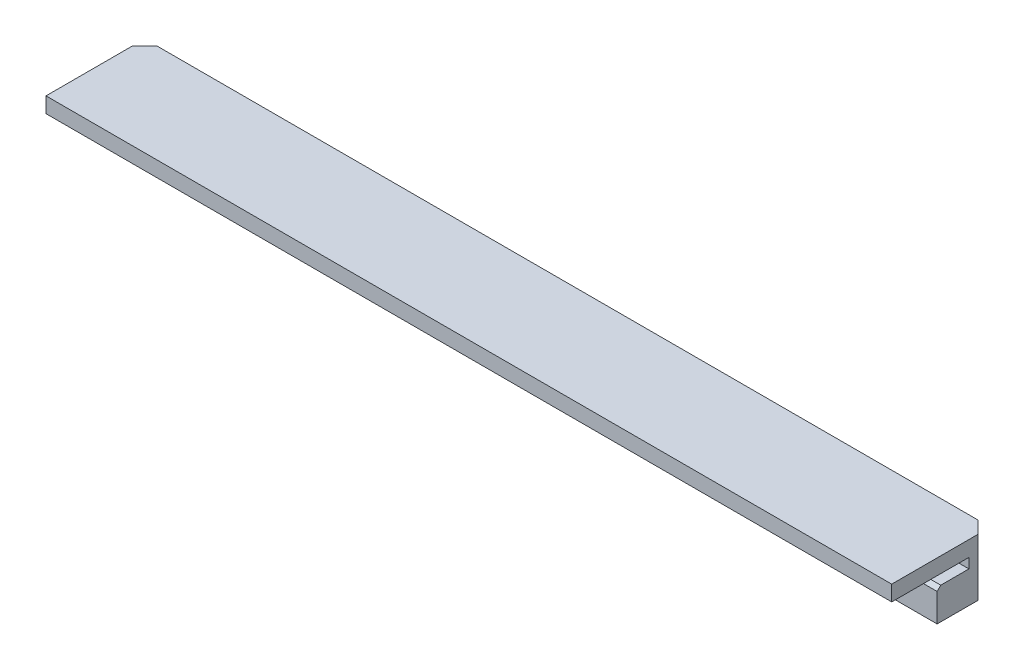
SolidWorks part; units mm, degrees
ref_plane "前视基准面" through (0, 0, 0) normal (0, 0, 1) x (1, 0, 0)
ref_plane "上视基准面" through (0, 0, 0) normal (0, 1, 0) x (1, 0, 0)
ref_plane "右视基准面" through (0, 0, 0) normal (1, 0, 0) x (0, 0, -1)
other "Configuration Table"
sketch "草图2" plane through (0, 0, 0) normal (0, 1, 0) x (1, 0, 0)
  line L1 (0, 0) -> (93.1, 0)
  line L2 (0, 0) -> (0, 10)
  line L3 (0, 10) -> (93.1, 10)
  line L4 (93.1, 0) -> (93.1, 10)
  dimension "D1" = 93.1
  dimension "D2" = 10
extrude "凸台-拉伸1" add sketch "草图2" along normal blind 3.5
sketch "草图4" plane through (0, 3.5, 0) normal (0, 1, 0) x (1, 0, 0)
  line L0 (93.1, 0) -> (93.1, 10) construction
  line L1 (0, 10) -> (93.1, 10)
  line L2 (0, 10) -> (0, 3.5)
  line L3 (0, 3.5) -> (93.1, 3.5)
  line L4 (93.1, 10) -> (93.1, 3.5)
  dimension "D1" = 6.5
extrude "凸台-拉伸2" add sketch "草图4" along normal blind 1.1
sketch "草图5" plane through (0, 4.6, 0) normal (0, 1, 0) x (1, 0, 0)
  line L0 (93.1, 3.5) -> (93.1, 10) construction
  line L1 (0, 10) -> (93.1, 10)
  line L2 (0, 10) -> (0, 0)
  line L3 (0, 0) -> (93.1, 0)
  line L4 (93.1, 10) -> (93.1, 0)
  dimension "D1" = 10
extrude "凸台-拉伸3" add sketch "草图5" along normal blind 2
sketch "草图6" plane through (0, 0, 0) normal (-1, 0, 0) x (0, 0, 1)
  line L0 (-10, 0) -> (-6.1895, 6.6)
  line L1 (-10, 0) -> (0, 0) construction
  line L2 (-10, 6.6) -> (-10, 0) construction
  line L3 (-10, 6.6) -> (0, 6.6) construction
  line L4 (-6.1895, 6.6) -> (-10, 6.6)
  line L5 (-10, 6.6) -> (-10, 0)
  dimension "D1" = 30
extrude "切除-拉伸1" cut sketch "草图6" against normal through all
sketch "草图7" plane through (0, 0, -3.5) normal (0, 0, 1) x (1, 0, 0)
  line L0 (0, 4.6) -> (93.1, 4.6) construction
  line L1 (5, 4.6) -> (88.1, 4.6)
  line L2 (5, 4.6) -> (5, 3.5)
  line L3 (5, 3.5) -> (88.1, 3.5)
  line L4 (88.1, 4.6) -> (88.1, 3.5)
  line L5 (0, 3.5) -> (93.1, 3.5) construction
  line L6 (0, 4.6) -> (0, 3.5) construction
  line L7 (93.1, 4.6) -> (93.1, 3.5) construction
  dimension "D1" = 5
  dimension "D2" = 5
extrude "凸台-拉伸4" add sketch "草图7" along normal up to surface (3.5 mm away) up to face at (46.55, 1.75, 0)
chamfer "倒角1" distance 0.4 angle 45 2 edges at (2.5, 3.5, 0) (90.6, 3.5, 0)
sketch "草图8" plane through (0, 0, 0) normal (0, -1, 0) x (1, 0, 0)
  line L0 (46.55, 147) -> (46.55, 0) construction
  line L1 (0, 0) -> (93.1, 0) construction
  line L2 (5, 0) -> (0, 0) construction
  circle A0 centre (46.55, 147) radius 150
  dimension "D1" = 300
  dimension "D2" = 147
extrude "切除-拉伸2" cut sketch "草图8" against normal up to next
sketch "草图9" plane through (0, 0, 0) normal (0, 0, 1) x (1, 0, 0)
  line L1 (0, 4.6) -> (93.1, 4.6)
  line L2 (0, 4.6) -> (0, 6.6)
  line L3 (0, 6.6) -> (93.1, 6.6)
  line L4 (93.1, 4.6) -> (93.1, 6.6)
extrude "凸台-拉伸5" add sketch "草图9" along normal blind 5 and the other way up to next
sketch "草图10" plane through (93.1, 0, 0) normal (1, 0, 0) x (0, 0, -1)
  line L0 (10, 0) -> (6.1895, 6.6) construction
  line L1 (-5, 6.6) -> (6.3627, 6.6)
  line L2 (-5, 6.6) -> (-5, 6.3)
  line L3 (-5, 6.3) -> (6.3627, 6.3)
  line L4 (6.3627, 6.6) -> (6.3627, 6.3)
  dimension "D1" = 0.3
extrude "切除-拉伸3" cut sketch "草图10" against normal up to next
sketch "草图11" plane through (93.1, 0, 0) normal (1, 0, 0) x (0, 0, -1)
  line L0 (6.3627, 6.3) -> (5.8627, 6.3)
  line L1 (-5, 6.3) -> (6.3627, 6.3) construction
  line L2 (5.8627, 6.3) -> (9.5, 0)
  line L3 (0, 0) -> (10, 0) construction
  line L4 (9.5, 0) -> (10, 0)
  line L5 (10, 0) -> (6.3627, 6.3)
  dimension "D1" = 0.5
extrude "切除-拉伸4" cut sketch "草图11" against normal up to next
sketch "草图12" plane through (0, 0, 0) normal (0, 1, 0) x (1, 0, 0)
  line L2 (0, -5) -> (93.1, -5) construction
  line L5 (46.55, 9.5) -> (46.55, -5) construction
  line L6 (0, 9.5) -> (93.1, 9.5) construction
  line L10 (0, 9.5) -> (5, 9.5)
  line L11 (5, 9.5) -> (0, 4.5)
  line L12 (0, 5.8627) -> (0, -5) construction
  line L13 (0, 4.5) -> (0, 9.5)
  line L14 (93.1, 4.5) -> (93.1, 9.5)
  line L15 (88.1, 9.5) -> (93.1, 4.5)
  line L16 (93.1, 9.5) -> (88.1, 9.5)
  dimension "D1" = 5
extrude "切除-拉伸5" cut sketch "草图12" along normal up to next
